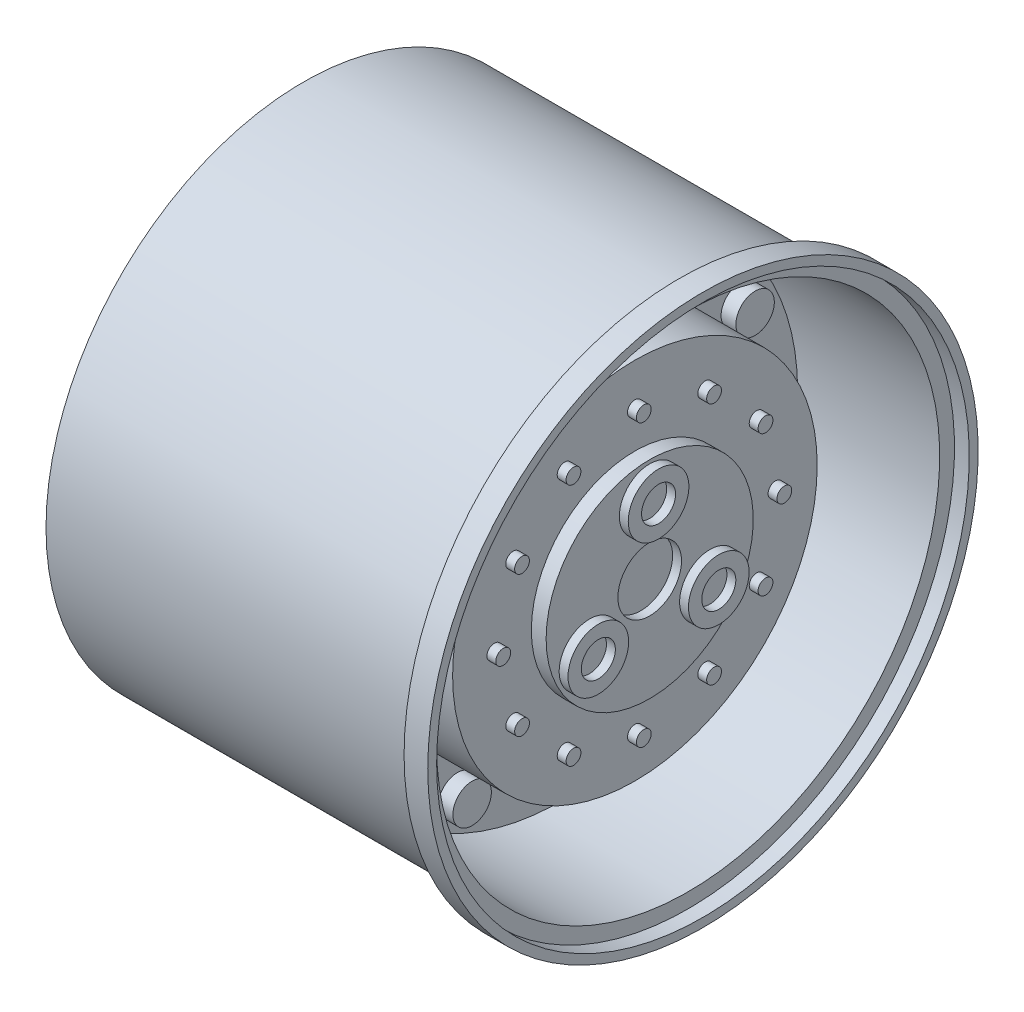
SolidWorks part; units mm, degrees
other "Markup1"
sketch "Sketch8" plane through (-88.9, 92.71, 92.71) normal (-0.7631, 0.6251, 0.1639) x (0.6077, 0.6079, 0.5111)
ref_plane "Front Plane" through (0, 0, 0) normal (0, 0, 1) x (1, 0, 0)
ref_plane "Top Plane" through (0, 0, 0) normal (0, 1, 0) x (1, 0, 0)
ref_plane "Right Plane" through (0, 0, 0) normal (1, 0, 0) x (0, 0, -1)
sketch "Sketch1" plane through (0, 0, 0) normal (0, 0, 1) x (1, 0, 0)
  line L0 (0, 0) -> (0, 118.2241) construction
  line L86 (0, 0) -> (149.7776, 0) construction
  line L87 (0, 0) -> (59.69, 0)
  line L88 (59.69, 0) -> (59.69, 44.45)
  line L89 (59.69, 44.45) -> (53.34, 44.45)
  line L92 (2.54, 101.6) -> (2.54, 107.95)
  line L93 (2.54, 107.95) -> (76.2, 107.95)
  line L94 (76.2, 107.95) -> (76.2, 114.3)
  line L95 (76.2, 114.3) -> (82.55, 114.3)
  line L96 (82.55, 114.3) -> (82.55, 118.11)
  line L97 (82.55, 118.11) -> (72.39, 118.11)
  line L98 (72.39, 118.11) -> (72.39, 110.49)
  line L99 (72.39, 110.49) -> (-88.9, 110.49)
  line L107 (-76.2, 0) -> (0, 0)
  line L108 (-88.9, 110.49) -> (-88.9, 105.41)
  line L109 (-88.9, 105.41) -> (-63.5, 105.41)
  line L110 (-63.5, 105.41) -> (-63.5, 101.6)
  line L111 (-63.5, 101.6) -> (-38.1, 101.6)
  line L112 (-38.1, 101.6) -> (-38.1, 78.74)
  line L113 (-38.1, 78.74) -> (-44.45, 78.74)
  line L114 (-44.45, 78.74) -> (-44.45, 64.77)
  line L115 (-44.45, 64.77) -> (-76.2, 64.77)
  line L116 (-76.2, 64.77) -> (-76.2, 0)
  line L117 (2.54, 101.6) -> (21.59, 101.6)
  line L118 (21.59, 101.6) -> (21.59, 78.232)
  line L119 (21.59, 78.232) -> (53.34, 78.232)
  line L120 (53.34, 78.232) -> (53.34, 44.45)
  dimension "D1" = 44.45
  dimension "D3" = 107.95
  dimension "D4" = 114.3
  dimension "D5" = 118.11
  dimension "D6" = 110.49
  dimension "D7" = 105.41
  dimension "D8" = 101.6
  dimension "D9" = 78.74
  dimension "D10" = 64.77
  dimension "D11" = 76.2
  dimension "D12" = 25.4
  dimension "D13" = 38.1
  dimension "D14" = 10.16
  dimension "D15" = 6.35
  dimension "D16" = 31.75
  dimension "D17" = 6.35
  dimension "D18" = 2.54
  dimension "D20" = 88.9
  dimension "D21" = 171.45
  dimension "D22" = 78.232
  dimension "D23" = 101.6
  dimension "D24" = 38.1
revolve "Revolve1" add sketch "Sketch1" angle 360 about L86
sketch "Sketch2" plane through (21.59, 0, 0) normal (1, 0, 0) x (0, 0, -1)
  circle A0 centre (0, 0) radius 88.9 construction
  circle A1 centre (0, 88.9) radius 8.255
  circle A2 centre (44.45, 76.9897) radius 8.255
  circle A3 centre (76.9897, 44.45) radius 8.255
  circle A4 centre (88.9, 0) radius 8.255
  circle A5 centre (76.9897, -44.45) radius 8.255
  circle A6 centre (44.45, -76.9897) radius 8.255
  circle A7 centre (0, -88.9) radius 8.255
  circle A8 centre (-44.45, -76.9897) radius 8.255
  circle A9 centre (-76.9897, -44.45) radius 8.255
  circle A10 centre (-88.9, 0) radius 8.255
  circle A11 centre (-76.9897, 44.45) radius 8.255
  circle A12 centre (-44.45, 76.9897) radius 8.255
  point P30 (0, 0)
  dimension "D1" = 177.8
  dimension "D2" = 16.51
  dimension "D3" = 12
extrude "Boss-Extrude1" add sketch "Sketch2" along normal blind 6.35
sketch "Sketch3" plane through (53.34, 0, 0) normal (1, 0, 0) x (0, 0, -1)
  circle A0 centre (0, 0) radius 60.325 construction
  circle A1 centre (0, 60.325) radius 3.175
  circle A2 centre (30.1625, 52.243) radius 3.175
  circle A3 centre (52.243, 30.1625) radius 3.175
  circle A4 centre (60.325, 0) radius 3.175
  circle A5 centre (52.243, -30.1625) radius 3.175
  circle A6 centre (30.1625, -52.243) radius 3.175
  circle A7 centre (0, -60.325) radius 3.175
  circle A8 centre (-30.1625, -52.243) radius 3.175
  circle A9 centre (-52.243, -30.1625) radius 3.175
  circle A10 centre (-60.325, 0) radius 3.175
  circle A11 centre (-52.243, 30.1625) radius 3.175
  circle A12 centre (-30.1625, 52.243) radius 3.175
  point P30 (0, 0)
  dimension "D1" = 120.65
  dimension "D2" = 6.35
  dimension "D3" = 12
extrude "Boss-Extrude2" add sketch "Sketch3" along normal blind 3.81
sketch "Sketch4" plane through (59.69, 0, 0) normal (1, 0, 0) x (0, 0, -1)
  circle A0 centre (0, 0) radius 13.6525
  dimension "D1" = 27.305
sketch "Sketch5" plane through (59.69, 0, 0) normal (1, 0, 0) x (0, 0, -1)
  circle A0 centre (0, 29.845) radius 13.0175
  circle A2 centre (0, 29.845) radius 7.3025
  circle A3 centre (25.8465, -14.9225) radius 13.0175
  circle A4 centre (25.8465, -14.9225) radius 7.3025
  circle A5 centre (-25.8465, -14.9225) radius 13.0175
  circle A6 centre (-25.8465, -14.9225) radius 7.3025
  point P14 (0, 0)
  dimension "D1" = 26.035
  dimension "D2" = 14.605
  dimension "D4" = 29.845
  dimension "D3" = 3
extrude "Boss-Extrude5" add sketch "Sketch5" along normal blind 3.81
extrude "Cut-Extrude1" cut sketch "Sketch4" against normal blind 3.81
sketch "Sketch6" plane through (-44.45, 0, 0) normal (-1, 0, 0) x (0, 0, 1)
  circle A0 centre (0, 69.85) radius 3.175
  circle A1 centre (34.925, 60.4919) radius 3.175
  circle A2 centre (60.4919, 34.925) radius 3.175
  circle A3 centre (69.85, 0) radius 3.175
  circle A4 centre (60.4919, -34.925) radius 3.175
  circle A5 centre (34.925, -60.4919) radius 3.175
  circle A6 centre (0, -69.85) radius 3.175
  circle A7 centre (-34.925, -60.4919) radius 3.175
  circle A8 centre (-60.4919, -34.925) radius 3.175
  circle A9 centre (-69.85, 0) radius 3.175
  circle A10 centre (-60.4919, 34.925) radius 3.175
  circle A11 centre (-34.925, 60.4919) radius 3.175
  point P28 (0, 0)
  dimension "D2" = 6.35
  dimension "D1" = 69.85
  dimension "D3" = 12
extrude "Boss-Extrude6" add sketch "Sketch6" along normal blind 3.81
sketch "Sketch7" plane through (-76.2, 0, 0) normal (-1, 0, 0) x (0, 0, 1)
  circle A0 centre (0, 0) radius 19.05
  dimension "D1" = 38.1
extrude "Cut-Extrude2" cut sketch "Sketch7" against normal up to surface (31.75 mm away) up to face at (-44.45, 60.4919, -38.1)
